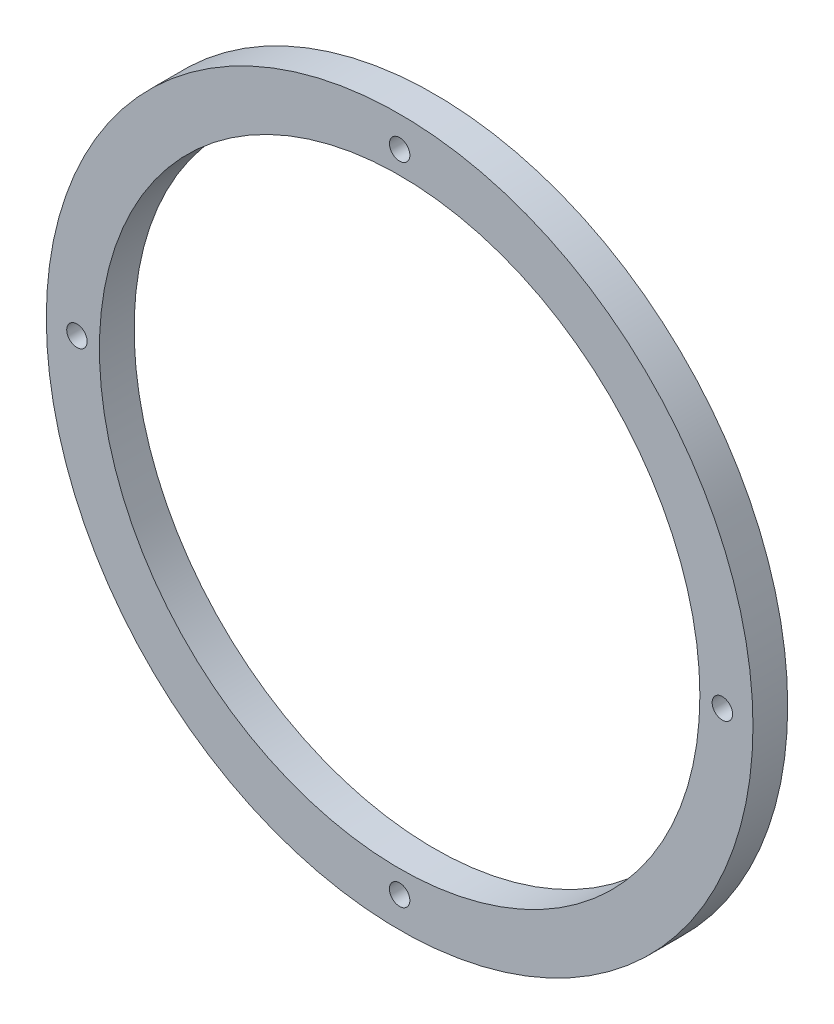
SolidWorks part; units mm, degrees
material "5052-O"
ref_plane "正面" through (0, 0, 0) normal (0, 0, 1) x (1, 0, 0)
ref_plane "平面" through (0, 0, 0) normal (0, 1, 0) x (1, 0, 0)
ref_plane "右側面" through (0, 0, 0) normal (1, 0, 0) x (0, 0, -1)
sketch "ｽｹｯﾁ1" plane through (0, 0, 0) normal (0, 0, 1) x (1, 0, 0)
  circle A0 centre (0, 0) radius 73.5
  circle A1 centre (0, 0) radius 86.5
  circle A2 centre (0, 0) radius 79 construction
  circle A3 centre (0, 79) radius 2.5
  circle A4 centre (79, 0) radius 2.5
  circle A5 centre (0, -79) radius 2.5
  circle A6 centre (-79, 0) radius 2.5
  point P16 (0, 0)
  dimension "D1" = 147
  dimension "D2" = 13
  dimension "D3" = 79
  dimension "D4" = 5
  dimension "D5" = 4
extrude "ﾎﾞｽ - 押し出し1" add sketch "ｽｹｯﾁ1" along normal blind 8.5 contours A1 A6 A2 A3 A4 A5 | A6 A2 A5 A4 A3 A0
hole_wizard "M4 丸皿ねじ用皿穴1" positions "ｽｹｯﾁ2" profile "ｽｹｯﾁ3" countersink size "M4" standard "JIS" end condition through all
sketch "ｽｹｯﾁ2" plane through (0, 0, 0) normal (0, 0, -1) x (-1, 0, 0)
  point P0 (-79, 0)
  point P3 (79, 0)
  point P6 (0, 79)
  point P9 (0, -79)
sketch "ｽｹｯﾁ3" plane through (79, 0, 0) normal (1, 0, 0) x (0, 1, 0)
  line L0 (0, 0) -> (0, 8.5)
  line L1 (0, 8.5) -> (2.4, 8.5)
  line L2 (2.4, 8.5) -> (2.4, 2.3)
  line L3 (2.4, 2.3) -> (4.7, 0)
  line L5 (4.7, 0) -> (0, 0)
  line L6 (-2.4, 2.3) -> (-4.7, 0) construction
  line L11 (0, -6.35) -> (0, 107.95) construction
  dimension "通し穴の直径" = 4.8
  dimension "通し穴の深さ" = 8.5
  dimension "表面の皿穴の直径" = 9.4
  dimension "表面の皿穴の角度" = 90
